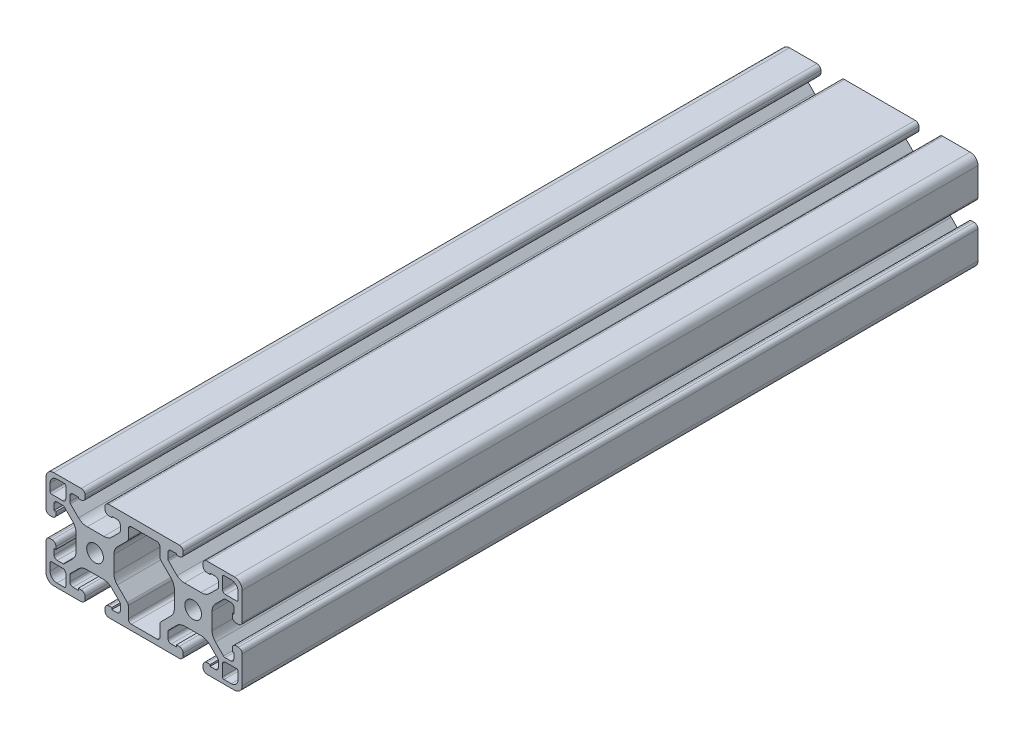
SolidWorks part; units mm, degrees
material "6105-T5 Aluminum"
ref_plane "Front Plane" through (0, 0, 0) normal (0, 0, 1) x (1, 0, 0)
ref_plane "Top Plane" through (0, 0, 0) normal (0, 1, 0) x (1, 0, 0)
ref_plane "Right Plane" through (0, 0, 0) normal (1, 0, 0) x (0, 0, -1)
sketch "Sketch1" plane through (0, 0, 0) normal (0, 0, 1) x (1, 0, 0)
  line L1 (-34.38, 20) -> (-5.62, 20)
  line L2 (-50.0243, -12.1998) -> (-46.7392, -8.9146)
  line L3 (-35.94, 17.51) -> (-35.94, 18.6069)
  line L4 (-30.9397, -6.7352) -> (-26.8324, -10.8426)
  line L5 (-32.3247, 3.3825) -> (-32.3289, -3.3756)
  line L6 (-26.8214, 10.8451) -> (-30.9313, 6.7404)
  line L7 (-26.4494, 15.43) -> (-26.4494, 11.7432)
  line L8 (-20, 16.6968) -> (-25.1787, 16.7)
  line L9 (-34.37, 15.94) -> (-33.1517, 15.94)
  line L10 (-33.1517, 16.4117) -> (-33.1517, 15.94)
  line L11 (-25.1904, -17.7174) -> (-14.8096, -17.7174)
  line L12 (-26.4604, -16.4474) -> (-26.4604, -11.7406)
  line L13 (-33.1517, 16.4117) -> (-31.0437, 16.4117)
  line L14 (-29.715, 12.8476) -> (-29.715, 15.1431)
  line L15 (-33.4586, 8.7397) -> (-29.9761, 12.2179)
  line L16 (-43.1872, 7.7) -> (-36.4245, 7.7)
  line L17 (-57.72, 11.94) -> (-53.21, 11.94)
  line L18 (-51.935, 13.21) -> (-51.935, 17.72)
  line L19 (-55.545, 18.35) -> (-52.565, 18.35)
  line L20 (-58.345, 15.55) -> (-58.345, 12.57)
  line L21 (-46.7456, 9.087) -> (-50.0243, 12.3658)
  line L22 (-50.285, 12.9951) -> (-50.285, 15.0869)
  line L23 (-49.015, 16.3569) -> (-46.8483, 16.3569)
  line L24 (-46.8483, 16.3569) -> (-46.8483, 15.8852)
  line L25 (-46.8483, 15.8852) -> (-45.63, 15.8852)
  line L26 (-44.06, 17.4552) -> (-44.06, 18.43)
  line L27 (-56.83, 20) -> (-45.63, 20)
  line L28 (-51.935, -17.72) -> (-51.935, -13.21)
  line L29 (-60, 16.83) -> (-60, 13)
  line L30 (-60, 5.5719) -> (-60, 13)
  line L31 (-58.4311, 4.06) -> (-57.51, 4.06)
  line L32 (-55.94, 5.63) -> (-55.94, 6.6964)
  line L33 (-56.715, 6.6964) -> (-55.94, 6.6964)
  line L34 (-56.715, 6.6964) -> (-56.715, 9.02)
  line L35 (-55.445, 10.29) -> (-53.1501, 10.29)
  line L36 (-52.5208, 10.0293) -> (-49.0912, 6.5998)
  line L37 (-47.7, 3.241) -> (-47.7, -3.241)
  line L38 (-52.5208, -10.0293) -> (-49.0912, -6.5998)
  line L39 (-55.445, -10.29) -> (-53.1501, -10.29)
  line L40 (-56.715, -9.02) -> (-56.715, -6.6964)
  line L41 (-55.94, -6.6964) -> (-56.715, -6.6964)
  line L42 (-55.94, -6.6964) -> (-55.94, -5.63)
  line L43 (-58.4311, -4.06) -> (-57.51, -4.06)
  line L44 (-60, -16.83) -> (-60, -5.5719)
  line L45 (-57.72, -11.94) -> (-53.21, -11.94)
  line L46 (-56.83, -20) -> (-45.6944, -20)
  line L47 (-34.3056, -20) -> (-26.9396, -20)
  line L48 (-49.015, -16.5584) -> (-46.8283, -16.5584)
  line L49 (-44.06, -17.4474) -> (-44.06, -18.3656)
  line L50 (-46.8283, -15.813) -> (-45.6944, -15.813)
  line L51 (-46.8283, -16.5584) -> (-46.8283, -15.813)
  line L52 (-50.285, -15.2884) -> (-50.285, -12.8291)
  line L53 (5.63, 20) -> (14.2818, 20)
  line L54 (-43.3804, -7.5234) -> (-36.6196, -7.5234)
  line L55 (-33.2608, -8.9146) -> (-29.9757, -12.1998)
  line L56 (-29.715, -12.8291) -> (-29.715, -15.3686)
  line L57 (-33.1717, -16.5584) -> (-31.0293, -16.5584)
  line L58 (-33.1717, -16.5584) -> (-33.1717, -15.813)
  line L59 (-34.3056, -15.813) -> (-33.1717, -15.813)
  line L60 (-35.94, -17.4474) -> (-35.94, -18.3656)
  line L61 (-26.9396, -20) -> (-13.0604, -20)
  line L62 (-13.0604, -20) -> (-5.6944, -20)
  line L63 (-59.8916, 0) -> (0, 0) construction
  line L64 (5.6944, -20) -> (14.3223, -20)
  line L65 (-4.06, -17.4474) -> (-4.06, -18.3656)
  line L66 (-6.8283, -15.813) -> (-5.6944, -15.813)
  line L67 (-6.8283, -16.5584) -> (-6.8283, -15.813)
  line L68 (-8.9707, -16.5584) -> (-6.8283, -16.5584)
  line L69 (-10.285, -12.8291) -> (-10.285, -15.3686)
  line L70 (-10.0243, -12.1998) -> (-6.7392, -8.9146)
  line L71 (3.3834, -7.5234) -> (-3.3804, -7.5234)
  line L72 (10.0243, -12.1998) -> (6.7392, -8.9146)
  line L73 (10.285, -15.2884) -> (10.285, -12.8291)
  line L74 (6.907, -16.5584) -> (9.015, -16.5584)
  line L75 (6.907, -15.8852) -> (6.907, -16.5584)
  line L76 (5.63, -15.8852) -> (6.907, -15.8852)
  line L77 (4.06, -18.4313) -> (4.06, -17.4552)
  line L78 (-13.1786, 10.8451) -> (-9.0687, 6.7404)
  line L79 (16.83, -20) -> (14.3223, -20)
  line L80 (20, -16.83) -> (20, -5.5696)
  line L81 (20, 5.5719) -> (20, 13)
  line L82 (17.51, -3.9996) -> (18.43, -3.9996)
  line L83 (15.94, -6.7799) -> (15.94, -5.5696)
  line L84 (16.5725, -6.7799) -> (15.94, -6.7799)
  line L85 (16.5725, -9.1555) -> (16.5725, -6.7799)
  line L86 (13.0076, -10.4255) -> (15.3025, -10.4255)
  line L87 (9.0891, -6.8716) -> (12.3778, -10.1644)
  line L88 (7.7, 3.241) -> (7.7, -3.515)
  line L89 (12.5208, 10.0293) -> (9.0912, 6.5998)
  line L90 (15.445, 10.29) -> (13.1501, 10.29)
  line L91 (16.715, 6.6964) -> (16.715, 9.02)
  line L92 (15.94, 6.6964) -> (16.715, 6.6964)
  line L93 (15.94, 5.63) -> (15.94, 6.6964)
  line L94 (18.4311, 4.06) -> (17.51, 4.06)
  line L95 (18.345, -15.55) -> (18.345, -12.57)
  line L96 (20, 16.83) -> (20, 13)
  line L97 (14.2818, 20) -> (16.83, 20)
  line L98 (11.935, -17.72) -> (11.935, -13.21)
  line L99 (4.06, 17.4552) -> (4.06, 18.43)
  line L100 (6.8483, 15.8852) -> (5.63, 15.8852)
  line L101 (6.8483, 16.3569) -> (6.8483, 15.8852)
  line L102 (9.015, 16.3569) -> (6.8483, 16.3569)
  line L103 (10.285, 12.9951) -> (10.285, 15.0869)
  line L104 (6.7456, 9.087) -> (10.0243, 12.3658)
  line L105 (18.345, 15.55) -> (18.345, 12.57)
  line L106 (12.565, 18.35) -> (15.545, 18.35)
  line L107 (11.935, 13.21) -> (11.935, 17.72)
  line L108 (17.72, 11.94) -> (13.21, 11.94)
  line L109 (3.1872, 7.7) -> (-3.5688, 7.7)
  line L110 (-6.5414, 8.7397) -> (-10.0239, 12.2179)
  line L111 (-10.285, 12.8476) -> (-10.285, 15.1431)
  line L112 (-8.9563, 16.4117) -> (-6.8483, 16.4117)
  line L113 (-13.5396, -16.4474) -> (-13.5396, -11.7406)
  line L114 (-58.345, -15.55) -> (-58.345, -12.57)
  line L115 (-6.8483, 16.4117) -> (-6.8483, 15.94)
  line L116 (-6.8483, 15.94) -> (-5.63, 15.94)
  line L117 (-20, 16.6968) -> (-14.8206, 16.7)
  line L118 (-13.5506, 15.43) -> (-13.5506, 11.7432)
  line L119 (-55.545, -18.35) -> (-52.565, -18.35)
  line L120 (-7.6753, 3.3825) -> (-7.6711, -3.3756)
  line L121 (-9.0624, -6.7373) -> (-13.1676, -10.8426)
  line L122 (-4.06, 17.51) -> (-4.06, 18.6069)
  line L129 (17.72, -11.94) -> (13.21, -11.94)
  line L131 (12.565, -18.35) -> (15.545, -18.35)
  line L133 (-40, 11.7412) -> (-40, -12.5149) construction
  line L134 (0, 12.6864) -> (0, -12.5149) construction
  line L135 (-40, 0) -> (-67.3415, -27.3415) construction
  arc A0 (-35.94, 18.6069) -> (-34.38, 20) centre (-34.38, 18.43) cw
  circle A1 centre (-40, 0) radius 3.4
  arc A2 (-34.37, 15.94) -> (-35.94, 17.51) centre (-34.37, 17.51) cw
  arc A3 (-31.0437, 16.4117) -> (-29.715, 15.1431) centre (-30.985, 15.1431) cw
  arc A4 (-33.4586, 8.7397) -> (-36.4245, 7.7) centre (-36.4245, 12.45) cw
  arc A5 (-43.1872, 7.7) -> (-46.7456, 9.087) centre (-43.3868, 12.4458) cw
  arc A6 (-32.3289, -3.3756) -> (-30.9397, -6.7352) centre (-27.5789, -3.3786) ccw
  arc A7 (-30.9313, 6.7404) -> (-32.3247, 3.3825) centre (-27.5747, 3.3795) ccw
  arc A8 (-26.8214, 10.8451) -> (-26.4494, 11.7432) centre (-27.7194, 11.7432) ccw
  arc A9 (-25.1787, 16.7) -> (-26.4494, 15.43) centre (-25.1794, 15.43) ccw
  arc A10 (-29.715, 12.8476) -> (-29.9761, 12.2179) centre (-30.605, 12.8476) cw
  arc A11 (-26.4604, -16.4474) -> (-25.1904, -17.7174) centre (-25.1904, -16.4474) ccw
  arc A12 (-26.4604, -11.7406) -> (-26.8324, -10.8426) centre (-27.7304, -11.7406) ccw
  arc A13 (-53.21, 11.94) -> (-51.935, 13.21) centre (-53.205, 13.21) ccw
  arc A14 (-51.935, 17.72) -> (-52.565, 18.35) centre (-52.565, 17.72) ccw
  arc A15 (-55.545, 18.35) -> (-58.345, 15.55) centre (-55.545, 15.55) ccw
  arc A16 (-58.345, 12.57) -> (-57.72, 11.94) centre (-57.715, 12.57) ccw
  arc A17 (-50.285, 12.9951) -> (-50.0243, 12.3658) centre (-49.395, 12.9951) ccw
  arc A18 (-49.015, 16.3569) -> (-50.285, 15.0869) centre (-49.015, 15.0869) ccw
  arc A19 (-45.63, 15.8852) -> (-44.06, 17.4552) centre (-45.63, 17.4552) ccw
  arc A20 (-44.06, 18.43) -> (-45.63, 20) centre (-45.63, 18.43) ccw
  arc A21 (-56.83, 20) -> (-60, 16.83) centre (-56.83, 16.83) ccw
  arc A22 (-60, 5.5719) -> (-58.4311, 4.06) centre (-58.4311, 5.63) ccw
  arc A23 (-57.51, 4.06) -> (-55.94, 5.63) centre (-57.51, 5.63) ccw
  arc A24 (-55.445, 10.29) -> (-56.715, 9.02) centre (-55.445, 9.02) ccw
  arc A25 (-52.5208, 10.0293) -> (-53.1501, 10.29) centre (-53.1501, 9.4) ccw
  arc A26 (-47.7, 3.241) -> (-49.0912, 6.5998) centre (-52.45, 3.241) ccw
  arc A27 (-47.7, -3.241) -> (-49.0912, -6.5998) centre (-52.45, -3.241) cw
  arc A28 (-52.5208, -10.0293) -> (-53.1501, -10.29) centre (-53.1501, -9.4) cw
  arc A29 (-55.445, -10.29) -> (-56.715, -9.02) centre (-55.445, -9.02) cw
  arc A30 (-57.51, -4.06) -> (-55.94, -5.63) centre (-57.51, -5.63) cw
  arc A31 (-60, -5.5719) -> (-58.4311, -4.06) centre (-58.4311, -5.63) cw
  arc A32 (-60, -16.83) -> (-56.83, -20) centre (-56.83, -16.83) ccw
  arc A33 (-44.06, -18.3656) -> (-45.6944, -20) centre (-45.6944, -18.3656) cw
  arc A34 (-45.6944, -15.813) -> (-44.06, -17.4474) centre (-45.6944, -17.4474) cw
  arc A35 (-50.285, -15.2884) -> (-49.015, -16.5584) centre (-49.015, -15.2884) ccw
  arc A36 (-50.0243, -12.1998) -> (-50.285, -12.8291) centre (-49.395, -12.8291) ccw
  arc A37 (-43.3804, -7.5234) -> (-46.7392, -8.9146) centre (-43.3804, -12.2734) ccw
  arc A38 (-33.2608, -8.9146) -> (-36.6196, -7.5234) centre (-36.6196, -12.2734) ccw
  arc A39 (-29.715, -12.8291) -> (-29.9757, -12.1998) centre (-30.605, -12.8291) ccw
  arc A40 (-31.0293, -16.5584) -> (-29.715, -15.3686) centre (-30.9825, -15.2892) ccw
  arc A41 (-34.3056, -15.813) -> (-35.94, -17.4474) centre (-34.3056, -17.4474) ccw
  arc A42 (-35.94, -18.3656) -> (-34.3056, -20) centre (-34.3056, -18.3656) ccw
  arc A43 (-4.06, -18.3656) -> (-5.6944, -20) centre (-5.6944, -18.3656) cw
  arc A44 (-5.6944, -15.813) -> (-4.06, -17.4474) centre (-5.6944, -17.4474) cw
  arc A45 (-8.9707, -16.5584) -> (-10.285, -15.3686) centre (-9.0175, -15.2892) cw
  arc A46 (-10.285, -12.8291) -> (-10.0243, -12.1998) centre (-9.395, -12.8291) cw
  arc A47 (-6.7392, -8.9146) -> (-3.3804, -7.5234) centre (-3.3804, -12.2734) cw
  arc A48 (3.3834, -7.5234) -> (6.7392, -8.9146) centre (3.3804, -12.2734) cw
  arc A49 (10.0243, -12.1998) -> (10.285, -12.8291) centre (9.395, -12.8291) cw
  arc A50 (10.285, -15.2884) -> (9.015, -16.5584) centre (9.015, -15.2884) cw
  arc A51 (4.06, -17.4552) -> (5.63, -15.8852) centre (5.63, -17.4552) cw
  arc A52 (5.6944, -20) -> (4.06, -18.4313) centre (5.63, -18.4313) cw
  arc A53 (20, -16.83) -> (16.83, -20) centre (16.83, -16.83) cw
  arc A54 (18.43, -3.9996) -> (20, -5.5696) centre (18.43, -5.5696) cw
  arc A55 (15.94, -5.5696) -> (17.51, -3.9996) centre (17.51, -5.5696) cw
  arc A56 (16.5725, -9.1555) -> (15.3025, -10.4255) centre (15.3025, -9.1555) cw
  arc A57 (13.0076, -10.4255) -> (12.3778, -10.1644) centre (13.0076, -9.5355) cw
  arc A58 (9.0891, -6.8716) -> (7.7, -3.515) centre (12.45, -3.515) cw
  arc A59 (7.7, 3.241) -> (9.0912, 6.5998) centre (12.45, 3.241) cw
  arc A60 (12.5208, 10.0293) -> (13.1501, 10.29) centre (13.1501, 9.4) cw
  arc A61 (15.445, 10.29) -> (16.715, 9.02) centre (15.445, 9.02) cw
  arc A62 (17.51, 4.06) -> (15.94, 5.63) centre (17.51, 5.63) cw
  arc A63 (20, 5.5719) -> (18.4311, 4.06) centre (18.4311, 5.63) cw
  arc A64 (16.83, 20) -> (20, 16.83) centre (16.83, 16.83) cw
  arc A65 (4.06, 18.43) -> (5.63, 20) centre (5.63, 18.43) cw
  arc A66 (5.63, 15.8852) -> (4.06, 17.4552) centre (5.63, 17.4552) cw
  arc A67 (9.015, 16.3569) -> (10.285, 15.0869) centre (9.015, 15.0869) cw
  arc A68 (10.285, 12.9951) -> (10.0243, 12.3658) centre (9.395, 12.9951) cw
  arc A69 (18.345, 12.57) -> (17.72, 11.94) centre (17.715, 12.57) cw
  arc A70 (15.545, 18.35) -> (18.345, 15.55) centre (15.545, 15.55) cw
  arc A71 (11.935, 17.72) -> (12.565, 18.35) centre (12.565, 17.72) cw
  arc A72 (13.21, 11.94) -> (11.935, 13.21) centre (13.205, 13.21) cw
  arc A73 (-13.5396, -11.7406) -> (-13.1676, -10.8426) centre (-12.2696, -11.7406) cw
  arc A74 (-13.5396, -16.4474) -> (-14.8096, -17.7174) centre (-14.8096, -16.4474) cw
  arc A75 (-10.285, 12.8476) -> (-10.0239, 12.2179) centre (-9.395, 12.8476) ccw
  arc A76 (-14.8206, 16.7) -> (-13.5506, 15.43) centre (-14.8206, 15.43) cw
  arc A77 (-13.1786, 10.8451) -> (-13.5506, 11.7432) centre (-12.2806, 11.7432) cw
  arc A78 (-9.0687, 6.7404) -> (-7.6753, 3.3825) centre (-12.4253, 3.3795) cw
  arc A79 (-7.6711, -3.3756) -> (-9.0624, -6.7373) centre (-12.4211, -3.3786) cw
  arc A80 (3.1872, 7.7) -> (6.7456, 9.087) centre (3.3868, 12.4458) ccw
  arc A81 (-6.5414, 8.7397) -> (-3.5688, 7.7) centre (-3.5755, 12.45) ccw
  arc A82 (-8.9563, 16.4117) -> (-10.285, 15.1431) centre (-9.015, 15.1431) ccw
  arc A83 (-5.63, 15.94) -> (-4.06, 17.51) centre (-5.63, 17.51) ccw
  circle A84 centre (0, 0) radius 3.4
  arc A85 (-4.06, 18.6069) -> (-5.62, 20) centre (-5.62, 18.43) ccw
  arc A86 (-58.345, -12.57) -> (-57.72, -11.94) centre (-57.715, -12.57) cw
  arc A87 (-55.545, -18.35) -> (-58.345, -15.55) centre (-55.545, -15.55) cw
  arc A88 (-51.935, -17.72) -> (-52.565, -18.35) centre (-52.565, -17.72) cw
  arc A89 (-53.21, -11.94) -> (-51.935, -13.21) centre (-53.205, -13.21) cw
  arc A90 (13.21, -11.94) -> (11.935, -13.21) centre (13.205, -13.21) ccw
  arc A91 (11.935, -17.72) -> (12.565, -18.35) centre (12.565, -17.72) ccw
  arc A92 (15.545, -18.35) -> (18.345, -15.55) centre (15.545, -15.55) ccw
  arc A93 (18.345, -12.57) -> (17.72, -11.94) centre (17.715, -12.57) ccw
  dimension "D2" = 6.8
  dimension "D1" = 40
  dimension "D3" = 40
  dimension "D4" = 8.12
  dimension "D5" = 80
  dimension "D6" = 3.3
  dimension "D7" = 12.3
  dimension "D8" = 45
  dimension "D9" = 20.57
  dimension "D10" = 4.06
  dimension "D15" = 1.5145
  dimension "D16" = 1.65
extrude "Extrude1" add sketch "Sketch1" against normal blind 300
